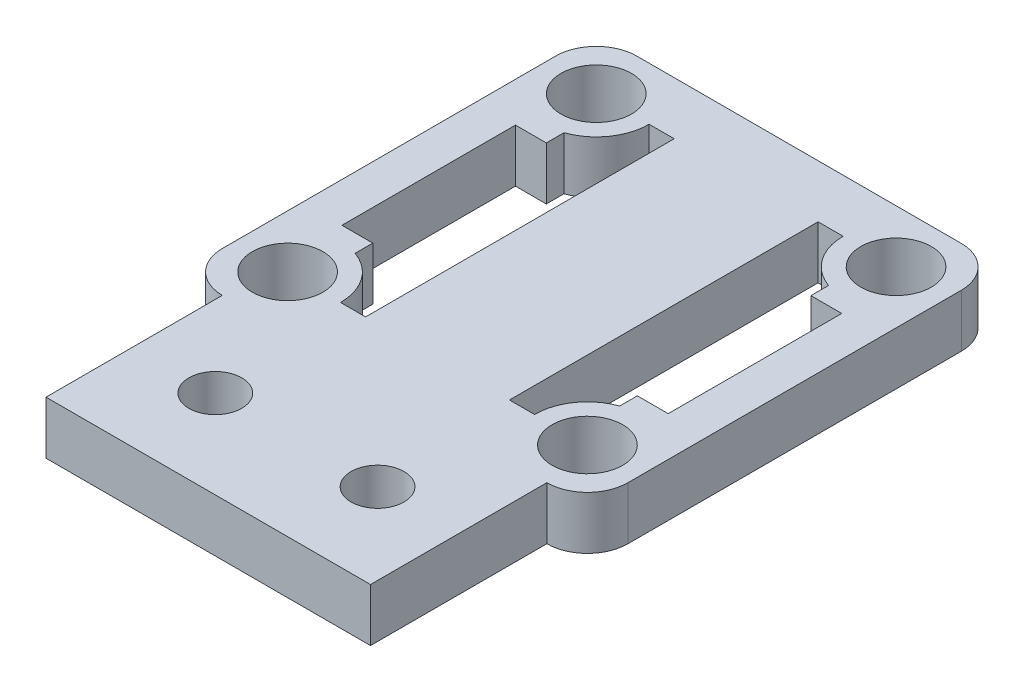
SolidWorks part; units mm, degrees
ref_plane "Front Plane" through (0, 0, 0) normal (0, 0, 1) x (1, 0, 0)
ref_plane "Top Plane" through (0, 0, 0) normal (0, 1, 0) x (1, 0, 0)
ref_plane "Right Plane" through (0, 0, 0) normal (1, 0, 0) x (0, 0, -1)
sketch "Sketch1" plane through (0, 0, 0) normal (0, 1, 0) x (1, 0, 0)
  line L1 (-12.6491, 14.6331) -> (5.7509, 14.6331)
  line L2 (-14.9491, 12.3331) -> (-14.9491, -6.5669)
  line L3 (-12.6491, -8.8669) -> (5.7509, -8.8669)
  line L4 (8.0509, 12.3331) -> (8.0509, -6.5669)
  line L5 (-14.9491, 14.6331) -> (8.0509, -8.8669) construction
  line L6 (-14.9491, -8.8669) -> (8.0509, 14.6331) construction
  arc A0 (8.0509, 12.3331) -> (5.7509, 14.6331) centre (5.7509, 12.3331) ccw
  arc A1 (-12.6491, -8.8669) -> (-14.9491, -6.5669) centre (-12.6491, -6.5669) cw
  arc A2 (5.7509, -8.8669) -> (8.0509, -6.5669) centre (5.7509, -6.5669) ccw
  arc A3 (-14.9491, 12.3331) -> (-12.6491, 14.6331) centre (-12.6491, 12.3331) cw
  point P0 (-3.4491, 2.8831)
  dimension "D3" = 2.3
  dimension "D4" = 2.3
  dimension "D1" = 23.5
  dimension "D2" = 23
extrude "Boss-Extrude1" add sketch "Sketch1" along normal blind 2
sketch "Sketch2" plane through (0, 2, 0) normal (0, 1, 0) x (1, 0, 0)
  line L8 (5.7509, 13.6331) -> (-12.6491, 13.6331)
  line L9 (-13.9491, 12.3331) -> (-13.9491, -6.5669)
  line L10 (-12.6491, -7.8669) -> (5.7509, -7.8669)
  line L11 (7.0509, -6.5669) -> (7.0509, 12.3331)
  line L12 (5.7509, 13.6331) -> (-12.6491, 13.6331)
  line L13 (-13.9491, 12.3331) -> (-13.9491, -6.5669)
  line L14 (-12.6491, -7.8669) -> (5.7509, -7.8669)
  line L15 (7.0509, -6.5669) -> (7.0509, 12.3331)
  arc A8 (7.0509, 12.3331) -> (5.7509, 13.6331) centre (5.7509, 12.3331) ccw
  arc A9 (-12.6491, 13.6331) -> (-13.9491, 12.3331) centre (-12.6491, 12.3331) ccw
  arc A10 (-13.9491, -6.5669) -> (-12.6491, -7.8669) centre (-12.6491, -6.5669) ccw
  arc A11 (5.7509, -7.8669) -> (7.0509, -6.5669) centre (5.7509, -6.5669) ccw
  arc A12 (7.0509, 12.3331) -> (5.7509, 13.6331) centre (5.7509, 12.3331) ccw
  arc A13 (-12.6491, 13.6331) -> (-13.9491, 12.3331) centre (-12.6491, 12.3331) ccw
  arc A14 (-13.9491, -6.5669) -> (-12.6491, -7.8669) centre (-12.6491, -6.5669) ccw
  arc A15 (5.7509, -7.8669) -> (7.0509, -6.5669) centre (5.7509, -6.5669) ccw
  dimension "D1" = 1
extrude "Cut-Extrude2" cut sketch "Sketch2" against normal blind 1
sketch "Sketch5" plane through (0, 1, 0) normal (0, 1, 0) x (1, 0, 0)
  line L0 (-3.4491, 13.6331) -> (-3.4491, -7.8669) construction
  line L1 (5.7509, 13.6331) -> (-12.6491, 13.6331) construction
  line L2 (-12.6491, -7.8669) -> (5.7509, -7.8669) construction
  line L3 (7.0509, 2.8831) -> (-13.9491, 2.8831) construction
  line L4 (7.0509, -6.5669) -> (7.0509, 12.3331) construction
  line L5 (-13.9491, 12.3331) -> (-13.9491, -6.5669) construction
  circle A0 centre (5.0509, 11.6331) radius 2
  circle A1 centre (5.0509, -5.8669) radius 2
  circle A2 centre (-11.9491, -5.8669) radius 2
  circle A3 centre (-11.9491, 11.6331) radius 2
  dimension "D1" = 4
extrude "Cut-Extrude3" cut sketch "Sketch5" against normal through all
sketch "Sketch6" plane through (0, 1, 0) normal (0, 1, 0) x (1, 0, 0)
  line L0 (-14.9491, 12.3331) -> (-14.9491, -6.5669) construction
  line L1 (8.0509, -6.5669) -> (8.0509, 12.3331) construction
  line L14 (4.0509, -5.8669) -> (4.0509, 11.6331)
  line L15 (4.0509, -3.0385) -> (4.0509, 8.8047)
  line L16 (2.0509, 11.6331) -> (2.0509, -5.8669)
  line L17 (-10.9491, 12.3331) -> (-10.9491, -6.5669)
  line L18 (-10.9491, 8.8047) -> (-10.9491, -3.0385)
  line L19 (-8.9491, 11.6331) -> (-8.9491, -5.8669)
  arc A5 (-11.9491, -8.8669) -> (-14.9491, -5.8669) centre (-11.9491, -5.8669) ccw
  arc A6 (-8.9491, -5.8669) -> (-10.9491, -3.0385) centre (-11.9491, -5.8669) ccw
  arc A20 (5.0509, 14.6331) -> (8.0509, 11.6331) centre (5.0509, 11.6331) ccw
  arc A21 (2.0509, 11.6331) -> (4.0509, 8.8047) centre (5.0509, 11.6331) ccw
  arc A23 (-14.9491, 11.6331) -> (-11.9491, 14.6331) centre (-11.9491, 11.6331) ccw
  arc A24 (-10.9491, 8.8047) -> (-8.9491, 11.6331) centre (-11.9491, 11.6331) ccw
  arc A26 (8.0509, -5.8669) -> (5.0509, -8.8669) centre (5.0509, -5.8669) ccw
  arc A27 (4.0509, -3.0385) -> (2.0509, -5.8669) centre (5.0509, -5.8669) ccw
  dimension "D1" = 23
  dimension "D2" = 1
  dimension "D3" = 1
  dimension "D4" = 1
  dimension "D5" = 1
  dimension "D6" = 3
  dimension "D7" = 3
extrude "Cut-Extrude4" cut sketch "Sketch6" against normal through all
sketch "Sketch7" plane through (0, 0, 8.8669) normal (0, 0, 1) x (1, 0, 0)
  line L0 (-14.9491, 2) -> (-14.9491, 0) construction
  line L1 (8.0509, 2) -> (8.0509, 0) construction
  line L2 (-12.6491, 2) -> (-12.6491, 0) construction
  line L3 (-12.6491, 1) -> (5.7509, 1)
  line L4 (5.7509, 2) -> (5.7509, 0) construction
  line L5 (5.7509, 1) -> (5.7509, 0)
  line L6 (5.7509, 0) -> (-12.6491, 0)
  line L7 (-12.6491, 0) -> (-12.6491, 1)
  line L8 (-12.6491, 2) -> (5.7509, 2) construction
  dimension "D1" = 23
extrude "Boss-Extrude2" add sketch "Sketch7" along normal blind 10
sketch "Sketch8" plane through (0, 1, 0) normal (0, 1, 0) x (1, 0, 0)
  line L0 (-12.6491, -8.8669) -> (5.7509, -8.8669) construction
  line L1 (-12.6491, -18.8669) -> (-12.6491, -8.8669) construction
  line L2 (5.7509, -18.8669) -> (5.7509, -8.8669) construction
  line L3 (-3.4491, -8.8669) -> (-3.4491, -18.8669) construction
  line L4 (5.7509, -18.8669) -> (-12.6491, -18.8669) construction
  circle A0 centre (1.1509, -13.8669) radius 1.5
  circle A1 centre (-8.0491, -13.8669) radius 1.5
  dimension "D2" = 3
  dimension "D1" = 5
  dimension "D3" = 18.4
  dimension "D4" = 4.6
  dimension "D5" = 4.6
extrude "Cut-Extrude5" cut sketch "Sketch8" against normal through all
sketch "Sketch9" plane through (0, 2, 0) normal (0, 1, 0) x (1, 0, 0)
  line L8 (5.7509, 13.8331) -> (-12.6491, 13.8331)
  line L9 (-14.1491, 12.3331) -> (-14.1491, -6.5669)
  line L10 (-12.6491, -8.0669) -> (5.7509, -8.0669)
  line L11 (7.2509, -6.5669) -> (7.2509, 12.3331)
  line L12 (5.7509, 13.8331) -> (-12.6491, 13.8331)
  line L13 (-14.1491, 12.3331) -> (-14.1491, -6.5669)
  line L14 (-12.6491, -8.0669) -> (5.7509, -8.0669)
  line L15 (7.2509, -6.5669) -> (7.2509, 12.3331)
  arc A8 (7.2509, 12.3331) -> (5.7509, 13.8331) centre (5.7509, 12.3331) ccw
  arc A9 (-12.6491, 13.8331) -> (-14.1491, 12.3331) centre (-12.6491, 12.3331) ccw
  arc A10 (-14.1491, -6.5669) -> (-12.6491, -8.0669) centre (-12.6491, -6.5669) ccw
  arc A11 (5.7509, -8.0669) -> (7.2509, -6.5669) centre (5.7509, -6.5669) ccw
  arc A12 (7.2509, 12.3331) -> (5.7509, 13.8331) centre (5.7509, 12.3331) ccw
  arc A13 (-12.6491, 13.8331) -> (-14.1491, 12.3331) centre (-12.6491, 12.3331) ccw
  arc A14 (-14.1491, -6.5669) -> (-12.6491, -8.0669) centre (-12.6491, -6.5669) ccw
  arc A15 (5.7509, -8.0669) -> (7.2509, -6.5669) centre (5.7509, -6.5669) ccw
  dimension "D1" = 0.8
extrude "Cut-Extrude6" cut sketch "Sketch9" against normal blind 1
sketch "Sketch11" plane through (0, 1, 0) normal (0, 1, 0) x (1, 0, 0)
  line L0 (-8.9491, 11.6331) -> (-7.528, 11.6331)
  line L1 (-7.528, 11.6331) -> (-7.528, -5.8669)
  line L2 (-7.528, -5.8669) -> (-8.9491, -5.8669)
  line L3 (-8.9491, -5.8669) -> (-8.9491, 11.6331)
  line L4 (-3.4491, 13.8331) -> (-3.4491, -8.0669) construction
  line L5 (5.7509, 13.8331) -> (-12.6491, 13.8331) construction
  line L6 (-12.6491, -8.0669) -> (5.7509, -8.0669) construction
  line L7 (0.6299, -5.8669) -> (2.0509, -5.8669)
  line L8 (0.6299, 11.6331) -> (0.6299, -5.8669)
  line L9 (2.0509, 11.6331) -> (0.6299, 11.6331)
  line L10 (2.0509, -5.8669) -> (2.0509, 11.6331)
  line L11 (-10.9491, 8.8047) -> (-10.9491, -3.0385) construction
  line L12 (-12.6991, 7.8031) -> (-10.9491, 7.8031)
  line L13 (-12.6991, 7.8031) -> (-12.6991, -2.0369)
  line L14 (-12.6991, -2.0369) -> (-10.9491, -2.0369)
  line L15 (-10.9491, 7.8031) -> (-10.9491, -2.0369)
  line L16 (5.8009, -2.0369) -> (4.0509, -2.0369)
  line L17 (4.0509, 7.8031) -> (4.0509, -2.0369)
  line L18 (5.8009, 7.8031) -> (4.0509, 7.8031)
  line L19 (5.8009, 7.8031) -> (5.8009, -2.0369)
  point P22 (-10.9491, 2.8831)
  point P23 (-10.9491, 2.8831)
  dimension "D1" = 9.84
  dimension "D2" = 1.75
extrude "Cut-Extrude7" cut sketch "Sketch11" against normal through all
sketch "Sketch12" plane through (0, 0, 0) normal (0, -1, 0) x (1, 0, 0)
  line L6 (8.0509, -12.3331) -> (8.0509, 6.5669)
  line L7 (5.7509, 8.8669) -> (5.7509, 18.8669)
  line L8 (5.7509, 18.8669) -> (-12.6491, 18.8669)
  line L9 (-12.6491, 18.8669) -> (-12.6491, 8.8669)
  line L10 (-14.9491, 6.5669) -> (-14.9491, -12.3331)
  line L11 (-12.6491, -14.6331) -> (5.7509, -14.6331)
  line L12 (8.0509, -12.3331) -> (8.0509, 6.5669)
  line L13 (5.7509, 8.8669) -> (5.7509, 18.8669)
  line L14 (5.7509, 18.8669) -> (-12.6491, 18.8669)
  line L15 (-12.6491, 18.8669) -> (-12.6491, 8.8669)
  line L16 (-14.9491, 6.5669) -> (-14.9491, -12.3331)
  line L17 (-12.6491, -14.6331) -> (5.7509, -14.6331)
  arc A4 (5.7509, -14.6331) -> (8.0509, -12.3331) centre (5.7509, -12.3331) ccw
  arc A5 (8.0509, 6.5669) -> (5.7509, 8.8669) centre (5.7509, 6.5669) ccw
  arc A6 (-12.6491, 8.8669) -> (-14.9491, 6.5669) centre (-12.6491, 6.5669) ccw
  arc A7 (-14.9491, -12.3331) -> (-12.6491, -14.6331) centre (-12.6491, -12.3331) ccw
  arc A8 (5.7509, -14.6331) -> (8.0509, -12.3331) centre (5.7509, -12.3331) ccw
  arc A9 (8.0509, 6.5669) -> (5.7509, 8.8669) centre (5.7509, 6.5669) ccw
  arc A10 (-12.6491, 8.8669) -> (-14.9491, 6.5669) centre (-12.6491, 6.5669) ccw
  arc A11 (-14.9491, -12.3331) -> (-12.6491, -14.6331) centre (-12.6491, -12.3331) ccw
  dimension "D1" = 0
extrude "Boss-Extrude3" add sketch "Sketch12" along normal blind 2
sketch "Sketch13" plane through (0, 0, 0) normal (0, 1, 0) x (1, 0, 0)
  line L8 (-12.6991, 7.8031) -> (-12.6991, -2.0369)
  line L9 (-12.6991, -2.0369) -> (-10.9491, -2.0369)
  line L10 (-10.9491, -2.0369) -> (-10.9491, -3.0385)
  line L11 (-8.9491, -5.8669) -> (-7.528, -5.8669)
  line L12 (-7.528, -5.8669) -> (-7.528, 11.6331)
  line L13 (-7.528, 11.6331) -> (-8.9491, 11.6331)
  line L14 (-10.9491, 8.8047) -> (-10.9491, 7.8031)
  line L15 (-10.9491, 7.8031) -> (-12.6991, 7.8031)
  line L16 (-12.6991, 7.8031) -> (-12.6991, -2.0369)
  line L17 (-12.6991, -2.0369) -> (-10.9491, -2.0369)
  line L18 (-10.9491, -2.0369) -> (-10.9491, -3.0385)
  line L19 (-8.9491, -5.8669) -> (-7.528, -5.8669)
  line L20 (-7.528, -5.8669) -> (-7.528, 11.6331)
  line L21 (-7.528, 11.6331) -> (-8.9491, 11.6331)
  line L22 (-10.9491, 8.8047) -> (-10.9491, 7.8031)
  line L23 (-10.9491, 7.8031) -> (-12.6991, 7.8031)
  arc A2 (-8.9491, -5.8669) -> (-10.9491, -3.0385) centre (-11.9491, -5.8669) ccw
  arc A3 (-10.9491, 8.8047) -> (-8.9491, 11.6331) centre (-11.9491, 11.6331) ccw
  arc A4 (-8.9491, -5.8669) -> (-10.9491, -3.0385) centre (-11.9491, -5.8669) ccw
  arc A5 (-10.9491, 8.8047) -> (-8.9491, 11.6331) centre (-11.9491, 11.6331) ccw
  dimension "D1" = 0
extrude "Cut-Extrude8" cut sketch "Sketch13" against normal through all both and the other way through all
sketch "Sketch14" plane through (0, 0, 0) normal (0, 1, 0) x (1, 0, 0)
  line L8 (0.6299, -5.8669) -> (2.0509, -5.8669)
  line L9 (4.0509, -3.0385) -> (4.0509, -2.0369)
  line L10 (4.0509, -2.0369) -> (5.8009, -2.0369)
  line L11 (5.8009, -2.0369) -> (5.8009, 7.8031)
  line L12 (5.8009, 7.8031) -> (4.0509, 7.8031)
  line L13 (4.0509, 7.8031) -> (4.0509, 8.8047)
  line L14 (2.0509, 11.6331) -> (0.6299, 11.6331)
  line L15 (0.6299, 11.6331) -> (0.6299, -5.8669)
  line L16 (0.6299, -5.8669) -> (2.0509, -5.8669)
  line L17 (4.0509, -3.0385) -> (4.0509, -2.0369)
  line L18 (4.0509, -2.0369) -> (5.8009, -2.0369)
  line L19 (5.8009, -2.0369) -> (5.8009, 7.8031)
  line L20 (5.8009, 7.8031) -> (4.0509, 7.8031)
  line L21 (4.0509, 7.8031) -> (4.0509, 8.8047)
  line L22 (2.0509, 11.6331) -> (0.6299, 11.6331)
  line L23 (0.6299, 11.6331) -> (0.6299, -5.8669)
  arc A2 (4.0509, -3.0385) -> (2.0509, -5.8669) centre (5.0509, -5.8669) ccw
  arc A3 (2.0509, 11.6331) -> (4.0509, 8.8047) centre (5.0509, 11.6331) ccw
  arc A4 (4.0509, -3.0385) -> (2.0509, -5.8669) centre (5.0509, -5.8669) ccw
  arc A5 (2.0509, 11.6331) -> (4.0509, 8.8047) centre (5.0509, 11.6331) ccw
  dimension "D1" = 0
extrude "Cut-Extrude9" cut sketch "Sketch14" against normal through all both and the other way through all
sketch "Sketch15" plane through (0, 0, 0) normal (0, 1, 0) x (1, 0, 0)
  circle A1 centre (-8.0491, -13.8669) radius 1.5
  circle A2 centre (-8.0491, -13.8669) radius 1.5
  dimension "D1" = 0
extrude "Cut-Extrude10" cut sketch "Sketch15" against normal through all both and the other way through all
sketch "Sketch16" plane through (0, 0, 0) normal (0, 1, 0) x (1, 0, 0)
  circle A1 centre (1.1509, -13.8669) radius 1.5
  circle A2 centre (1.1509, -13.8669) radius 1.5
  dimension "D1" = 0
extrude "Cut-Extrude11" cut sketch "Sketch16" against normal through all both and the other way through all
sketch "Sketch17" plane through (0, 0, 0) normal (0, 1, 0) x (1, 0, 0)
  circle A0 centre (-11.9491, -5.8669) radius 2 construction
  circle A1 centre (5.0509, -5.8669) radius 2 construction
  circle A2 centre (-11.9491, 11.6331) radius 2 construction
  circle A3 centre (5.0509, 11.6331) radius 2 construction
  circle A4 centre (-11.9491, -5.8669) radius 2
  circle A5 centre (5.0509, -5.8669) radius 2
  circle A6 centre (-11.9491, 11.6331) radius 2
  circle A7 centre (5.0509, 11.6331) radius 2
extrude "Cut-Extrude12" cut sketch "Sketch17" against normal through all both and the other way through all
sketch "Sketch18" plane through (0, 1, 0) normal (0, 1, 0) x (1, 0, 0)
  line L4 (5.7509, 13.8331) -> (-12.6491, 13.8331)
  line L5 (-14.1491, 12.3331) -> (-14.1491, -6.5669)
  line L6 (-12.6491, -8.0669) -> (5.7509, -8.0669)
  line L7 (7.2509, -6.5669) -> (7.2509, 12.3331)
  line L8 (5.7509, 13.8331) -> (-12.6491, 13.8331)
  line L9 (-14.1491, 12.3331) -> (-14.1491, -6.5669)
  line L10 (-12.6491, -8.0669) -> (5.7509, -8.0669)
  line L11 (7.2509, -6.5669) -> (7.2509, 12.3331)
  arc A4 (7.2509, 12.3331) -> (5.7509, 13.8331) centre (5.7509, 12.3331) ccw
  arc A5 (-12.6491, 13.8331) -> (-14.1491, 12.3331) centre (-12.6491, 12.3331) ccw
  arc A6 (-14.1491, -6.5669) -> (-12.6491, -8.0669) centre (-12.6491, -6.5669) ccw
  arc A7 (5.7509, -8.0669) -> (7.2509, -6.5669) centre (5.7509, -6.5669) ccw
  arc A8 (7.2509, 12.3331) -> (5.7509, 13.8331) centre (5.7509, 12.3331) ccw
  arc A9 (-12.6491, 13.8331) -> (-14.1491, 12.3331) centre (-12.6491, 12.3331) ccw
  arc A10 (-14.1491, -6.5669) -> (-12.6491, -8.0669) centre (-12.6491, -6.5669) ccw
  arc A11 (5.7509, -8.0669) -> (7.2509, -6.5669) centre (5.7509, -6.5669) ccw
  dimension "D1" = 0
extrude "Boss-Extrude4" add sketch "Sketch18" along normal up to surface (1 mm away) up to face at (-3.4491, 2, -2.8831)
sketch "Sketch19" plane through (0, 1, 0) normal (0, -1, 0) x (1, 0, 0)
  line L8 (-10.9491, 3.0385) -> (-10.9491, 2.0369)
  line L9 (-10.9491, 2.0369) -> (-12.6991, 2.0369)
  line L10 (-12.6991, 2.0369) -> (-12.6991, -7.8031)
  line L11 (-12.6991, -7.8031) -> (-10.9491, -7.8031)
  line L12 (-10.9491, -7.8031) -> (-10.9491, -8.8047)
  line L13 (-8.9491, -11.6331) -> (-7.528, -11.6331)
  line L14 (-7.528, -11.6331) -> (-7.528, 5.8669)
  line L15 (-7.528, 5.8669) -> (-8.9491, 5.8669)
  line L16 (-10.9491, 3.0385) -> (-10.9491, 2.0369)
  line L17 (-10.9491, 2.0369) -> (-12.6991, 2.0369)
  line L18 (-12.6991, 2.0369) -> (-12.6991, -7.8031)
  line L19 (-12.6991, -7.8031) -> (-10.9491, -7.8031)
  line L20 (-10.9491, -7.8031) -> (-10.9491, -8.8047)
  line L21 (-8.9491, -11.6331) -> (-7.528, -11.6331)
  line L22 (-7.528, -11.6331) -> (-7.528, 5.8669)
  line L23 (-7.528, 5.8669) -> (-8.9491, 5.8669)
  line L24 (4.0509, 2.0369) -> (4.0509, 3.0385)
  line L25 (2.0509, 5.8669) -> (0.6299, 5.8669)
  line L26 (0.6299, 5.8669) -> (0.6299, -11.6331)
  line L27 (0.6299, -11.6331) -> (2.0509, -11.6331)
  line L28 (4.0509, -8.8047) -> (4.0509, -7.8031)
  line L29 (4.0509, -7.8031) -> (5.8009, -7.8031)
  line L30 (5.8009, -7.8031) -> (5.8009, 2.0369)
  line L31 (5.8009, 2.0369) -> (4.0509, 2.0369)
  line L32 (4.0509, 2.0369) -> (4.0509, 3.0385)
  line L33 (2.0509, 5.8669) -> (0.6299, 5.8669)
  line L34 (0.6299, 5.8669) -> (0.6299, -11.6331)
  line L35 (0.6299, -11.6331) -> (2.0509, -11.6331)
  line L36 (4.0509, -8.8047) -> (4.0509, -7.8031)
  line L37 (4.0509, -7.8031) -> (5.8009, -7.8031)
  line L38 (5.8009, -7.8031) -> (5.8009, 2.0369)
  line L39 (5.8009, 2.0369) -> (4.0509, 2.0369)
  circle A0 centre (5.0509, -11.6331) radius 2 construction
  circle A1 centre (-11.9491, -11.6331) radius 2 construction
  arc A2 (-8.9491, -11.6331) -> (-10.9491, -8.8047) centre (-11.9491, -11.6331) ccw
  arc A3 (-10.9491, 3.0385) -> (-8.9491, 5.8669) centre (-11.9491, 5.8669) ccw
  arc A4 (-8.9491, -11.6331) -> (-10.9491, -8.8047) centre (-11.9491, -11.6331) ccw
  arc A5 (-10.9491, 3.0385) -> (-8.9491, 5.8669) centre (-11.9491, 5.8669) ccw
  arc A6 (2.0509, 5.8669) -> (4.0509, 3.0385) centre (5.0509, 5.8669) ccw
  arc A7 (4.0509, -8.8047) -> (2.0509, -11.6331) centre (5.0509, -11.6331) ccw
  arc A8 (2.0509, 5.8669) -> (4.0509, 3.0385) centre (5.0509, 5.8669) ccw
  arc A9 (4.0509, -8.8047) -> (2.0509, -11.6331) centre (5.0509, -11.6331) ccw
  circle A10 centre (-11.9491, 5.8669) radius 2 construction
  circle A11 centre (5.0509, 5.8669) radius 2 construction
  circle A12 centre (5.0509, -11.6331) radius 2
  circle A13 centre (-11.9491, -11.6331) radius 2
  circle A14 centre (-11.9491, 5.8669) radius 2
  circle A15 centre (5.0509, 5.8669) radius 2
  dimension "D1" = 0
  dimension "D2" = 0
extrude "Cut-Extrude13" cut sketch "Sketch19" against normal through all both and the other way through all
sketch "Sketch20" plane through (0, 2, 0) normal (0, 1, 0) x (1, 0, 0)
  line L4 (5.7509, 14.6331) -> (-12.6491, 14.6331)
  line L5 (-14.9491, 12.3331) -> (-14.9491, -6.5669)
  line L6 (-12.6491, -8.8669) -> (5.7509, -8.8669)
  line L7 (8.0509, -6.5669) -> (8.0509, 12.3331)
  line L8 (5.7509, 14.6331) -> (-12.6491, 14.6331)
  line L9 (-14.9491, 12.3331) -> (-14.9491, -6.5669)
  line L10 (-12.6491, -8.8669) -> (5.7509, -8.8669)
  line L11 (8.0509, -6.5669) -> (8.0509, 12.3331)
  arc A4 (8.0509, 12.3331) -> (5.7509, 14.6331) centre (5.7509, 12.3331) ccw
  arc A5 (-12.6491, 14.6331) -> (-14.9491, 12.3331) centre (-12.6491, 12.3331) ccw
  arc A6 (-14.9491, -6.5669) -> (-12.6491, -8.8669) centre (-12.6491, -6.5669) ccw
  arc A7 (5.7509, -8.8669) -> (8.0509, -6.5669) centre (5.7509, -6.5669) ccw
  arc A8 (8.0509, 12.3331) -> (5.7509, 14.6331) centre (5.7509, 12.3331) ccw
  arc A9 (-12.6491, 14.6331) -> (-14.9491, 12.3331) centre (-12.6491, 12.3331) ccw
  arc A10 (-14.9491, -6.5669) -> (-12.6491, -8.8669) centre (-12.6491, -6.5669) ccw
  arc A11 (5.7509, -8.8669) -> (8.0509, -6.5669) centre (5.7509, -6.5669) ccw
  dimension "D1" = 0
extrude "Cut-Extrude14" cut sketch "Sketch20" against normal blind 1
